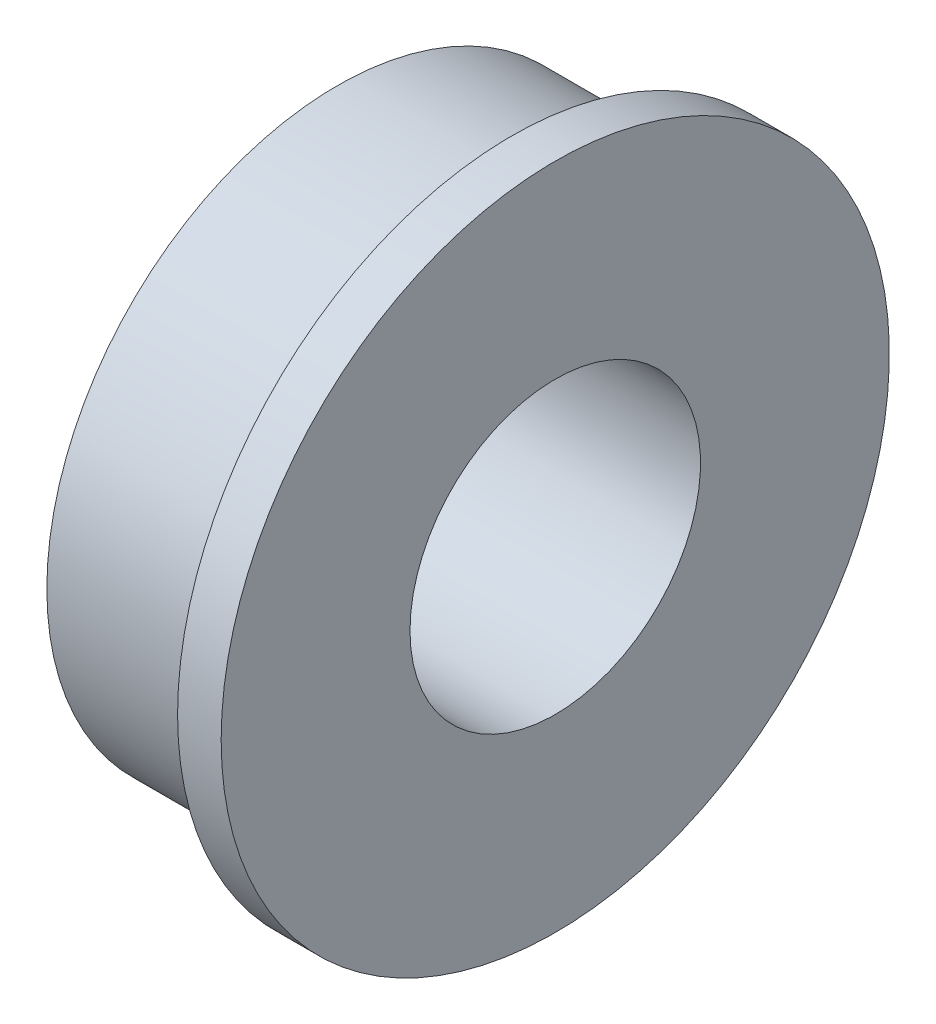
SolidWorks part; units mm, degrees
ref_plane "Front Plane" through (0, 0, 0) normal (0, 0, 1) x (1, 0, 0)
ref_plane "Top Plane" through (0, 0, 0) normal (0, 1, 0) x (1, 0, 0)
ref_plane "Right Plane" through (0, 0, 0) normal (1, 0, 0) x (0, 0, -1)
sketch "Sketch1" plane through (0, 0, 0) normal (0, 0, 1) x (1, 0, 0)
  line L0 (0, 2) -> (3, 2)
  line L1 (3, 2) -> (3, 4.6)
  line L2 (3, 4.6) -> (2.4, 4.6)
  line L3 (2.4, 4.6) -> (2.4, 4)
  line L4 (2.4, 4) -> (0, 4)
  line L5 (0, 4) -> (0, 2)
  line L6 (0, 0) -> (3, 0) construction
  dimension "D1" = 3
  dimension "D2" = 2
  dimension "D3" = 4
  dimension "D4" = 0.6
  dimension "D5" = 4.6
revolve "Revolve1" add sketch "Sketch1" angle 360 about L6
